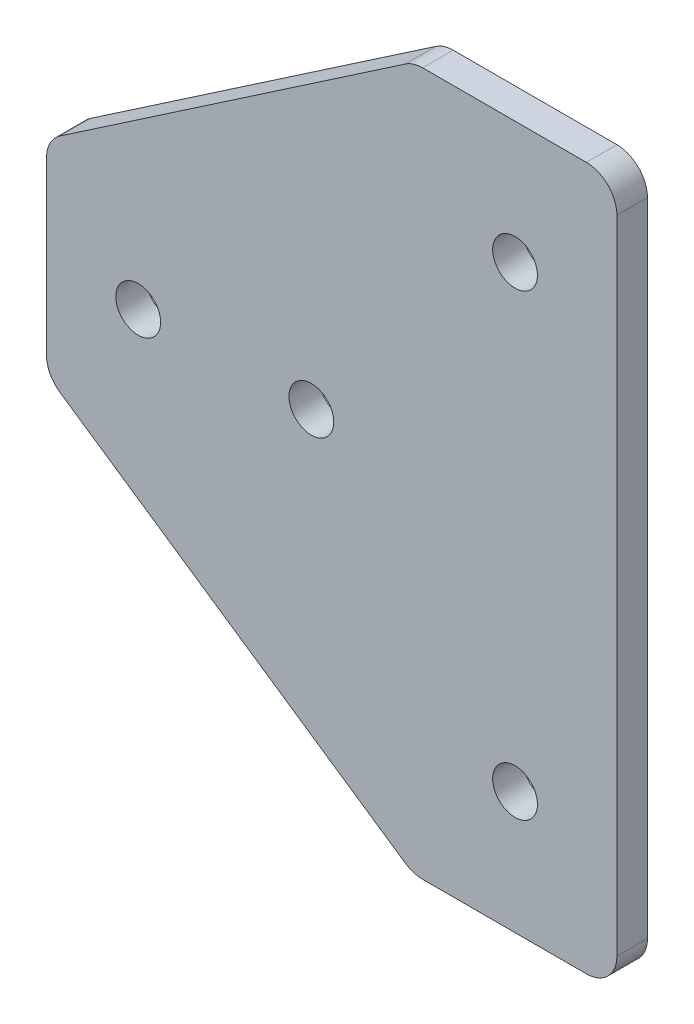
SolidWorks part; units mm, degrees
material "ABS"
ref_plane "Front Plane" through (0, 0, 0) normal (0, 0, 1) x (1, 0, 0)
ref_plane "Top Plane" through (0, 0, 0) normal (0, 1, 0) x (1, 0, 0)
ref_plane "Right Plane" through (0, 0, 0) normal (1, 0, 0) x (0, 0, -1)
sketch "Sketch1" plane through (0, 0, 0) normal (0, 0, 1) x (1, 0, 0)
  line L0 (0, -34.5) -> (0, 34.5)
  line L1 (0, 34.5) -> (-20, 34.5)
  line L2 (-20, 34.5) -> (-56, 10)
  line L3 (-56, 10) -> (-56, -10)
  line L4 (-56, -10) -> (-20, -34.5)
  line L5 (-20, -34.5) -> (0, -34.5)
  line L6 (-56, 0) -> (0, 0) construction
  dimension "D1" = 20
  dimension "D2" = 20
  dimension "D3" = 69
  dimension "D4" = 56
extrude "Boss-Extrude1" add sketch "Sketch1" along normal blind 3
sketch "Sketch2" plane through (0, 0, 3) normal (0, 0, 1) x (1, 0, 0)
  line L0 (-56, 0) -> (-47, 0) construction
  line L1 (-56, 10) -> (-56, -10) construction
  line L2 (0, -34.5) -> (0, 34.5) construction
  line L3 (-10, 22.5) -> (-10, -22.5) construction
  line L4 (-10, 0) -> (0, 0) construction
  circle A0 centre (-47, 0) radius 2.2
  circle A1 centre (-30, 0) radius 2.2
  circle A2 centre (-10, 22.5) radius 2.2
  circle A3 centre (-10, -22.5) radius 2.2
  dimension "D1" = 4.4
  dimension "D2" = 17
  dimension "D3" = 9
  dimension "D4" = 45
  dimension "D5" = 10
extrude "Cut-Extrude1" cut sketch "Sketch2" against normal through all
fillet "Fillet1" radius 3 6 edges at (0, -34.5, 1.5) (-20, -34.5, 1.5) (-56, -10, 1.5) (-56, 10, 1.5) (-20, 34.5, 1.5) (0, 34.5, 1.5)
